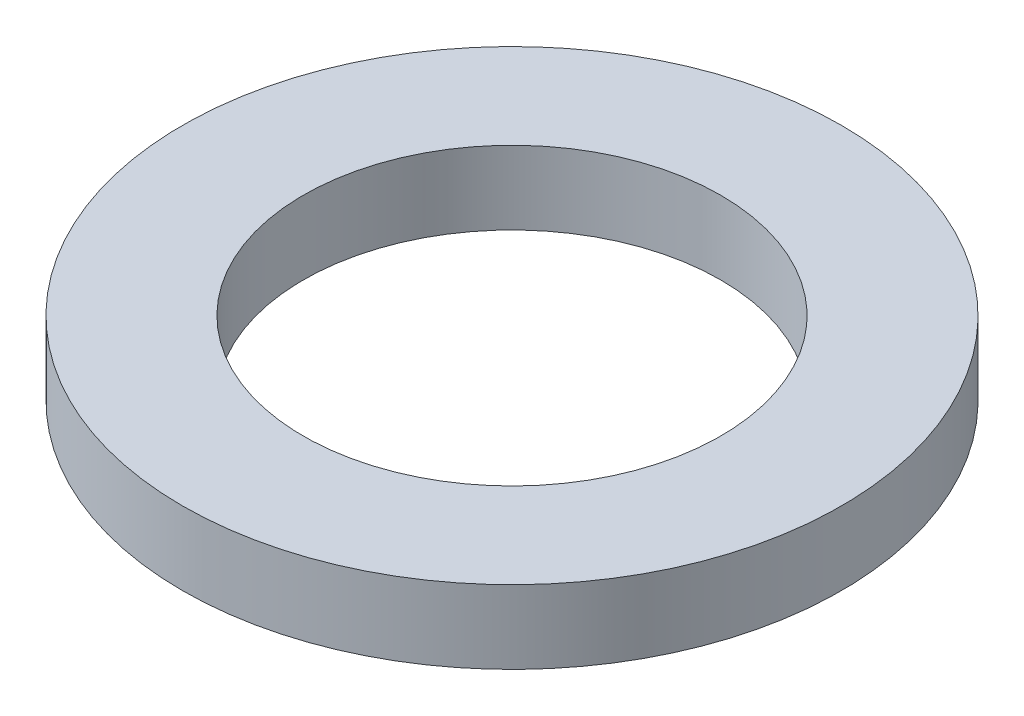
SolidWorks part; units mm, degrees
ref_plane "Ebene vorne" through (0, 0, 0) normal (0, 0, 1) x (1, 0, 0)
ref_plane "Ebene oben" through (0, 0, 0) normal (0, 1, 0) x (1, 0, 0)
ref_plane "Ebene rechts" through (0, 0, 0) normal (1, 0, 0) x (0, 0, -1)
sketch "Skizze1" plane through (0, 0, 0) normal (1, 0, 0) x (0, 0, -1)
  line L0 (0, 0) -> (0, 139.5201) construction
  line L1 (23, 98.2962) -> (-23, 98.2962) construction
  line L2 (-22.9, 103.3962) -> (-14.5, 103.3962)
  line L3 (-22.9, 103.3962) -> (-22.9, 98.2962)
  line L4 (-22.9, 98.2962) -> (-14.5, 98.2962)
  line L5 (-14.5, 103.3962) -> (-14.5, 98.2962)
  dimension "D1" = 29
  dimension "D2" = 45.8
  dimension "D3" = 5.1
revolve "Rotation1" add sketch "Skizze1" angle 360 about L0
